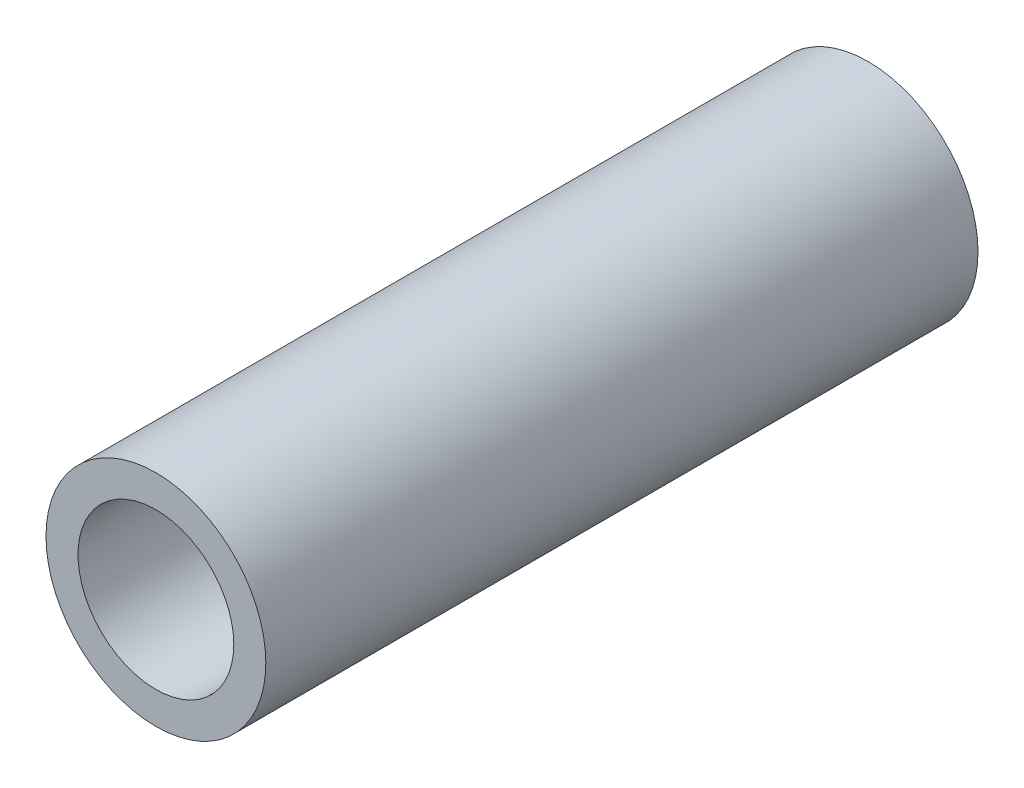
SolidWorks part; units mm, degrees
material "Nylon 101"
ref_plane "Front Plane" through (0, 0, 0) normal (0, 0, 1) x (1, 0, 0)
ref_plane "Top Plane" through (0, 0, 0) normal (0, 1, 0) x (1, 0, 0)
ref_plane "Right Plane" through (0, 0, 0) normal (1, 0, 0) x (0, 0, -1)
sketch "Sketch1" plane through (0, 0, 0) normal (0, 0, 1) x (1, 0, 0)
  circle A0 centre (0, 0) radius 2.25
  circle A1 centre (0, 0) radius 3.175
  dimension "D1" = 4.5
  dimension "D2" = 6.35
extrude "Boss-Extrude1" add sketch "Sketch1" along normal blind 20.574
